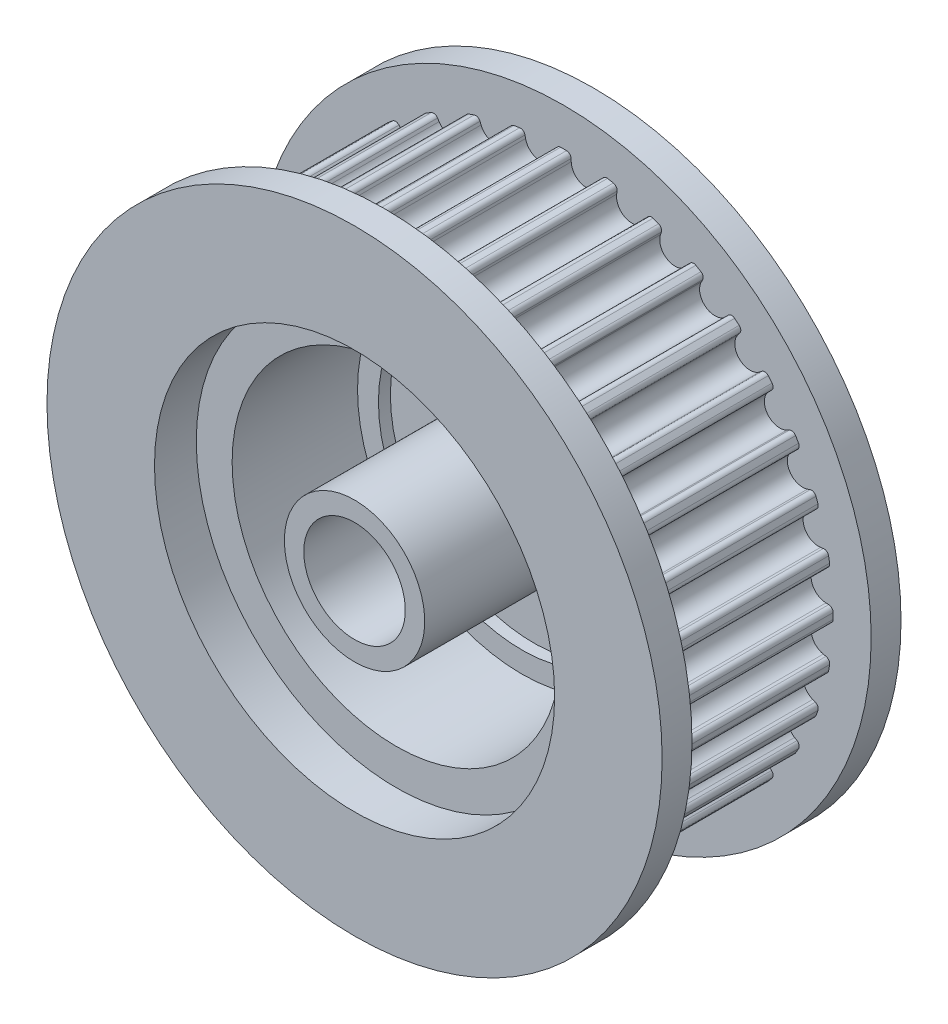
SolidWorks part; units mm, degrees
ref_plane "前视基准面" through (0, 0, 0) normal (0, 0, 1) x (1, 0, 0)
ref_plane "上视基准面" through (0, 0, 0) normal (0, 1, 0) x (1, 0, 0)
ref_plane "右视基准面" through (0, 0, 0) normal (1, 0, 0) x (0, 0, -1)
sketch "Sketch2" plane through (0, 0, 0) normal (0, 0, 1) x (1, 0, 0)
  circle A0 centre (0, 0) radius 45.15
  dimension "D1" = 90.3
extrude "Extrude1" add sketch "Sketch2" along normal mid plane 30
sketch "Sketch1" plane through (0, 0, 15) normal (0, 0, 1) x (1, 0, 0)
  line L0 (0, 0) -> (0, 45.835) construction
  line L1 (0, 0) -> (-3.9948, 45.6606) construction
  line L2 (-1.2656, 44.3946) -> (-1.2821, 43.9222)
  line L3 (-6.4627, 43.9399) -> (-6.3644, 43.4775)
  circle A0 centre (0, 0) radius 45.835 construction
  arc A1 (-0.4946, 45.1473) -> (-7.3526, 44.5473) centre (0, 0) ccw
  arc A2 (-6.3644, 43.4775) -> (-1.2821, 43.9222) centre (-3.8505, 44.0119) ccw
  arc A3 (-0.4946, 45.1473) -> (-1.2656, 44.3946) centre (-0.4861, 44.3673) ccw
  arc A4 (-7.3526, 44.5473) -> (-6.4627, 43.9399) centre (-7.2256, 43.7777) cw
  point P4 (45.6606, 3.9948)
  point P5 (44.2732, 11.863)
  point P6 (41.5406, 19.3707)
  point P7 (37.5458, 26.2899)
  point P8 (32.4102, 32.4102)
  point P9 (26.2899, 37.5458)
  point P10 (19.3707, 41.5406)
  point P11 (11.863, 44.2732)
  point P12 (3.9948, 45.6606)
  point P13 (-3.9948, 45.6606)
  point P14 (-11.863, 44.2732)
  point P15 (-19.3707, 41.5406)
  point P16 (-26.2899, 37.5458)
  point P17 (-32.4102, 32.4102)
  point P18 (-37.5458, 26.2899)
  point P19 (-41.5406, 19.3707)
  point P20 (-44.2732, 11.863)
  point P21 (-45.6606, 3.9948)
  point P22 (-45.6606, -3.9948)
  point P23 (-44.2732, -11.863)
  point P24 (-41.5406, -19.3707)
  point P25 (-37.5458, -26.2899)
  point P26 (-32.4102, -32.4102)
  point P27 (-26.2899, -37.5458)
  point P28 (-19.3707, -41.5406)
  point P29 (-11.863, -44.2732)
  point P30 (-3.9948, -45.6606)
  point P31 (3.9948, -45.6606)
  point P32 (11.863, -44.2732)
  point P33 (19.3707, -41.5406)
  point P34 (26.2899, -37.5458)
  point P35 (32.4102, -32.4102)
  point P36 (37.5458, -26.2899)
  point P37 (41.5406, -19.3707)
  point P38 (44.2732, -11.863)
  point P39 (45.6606, -3.9948)
  dimension "D1" = 91.67
  dimension "D2" = 90.3
  dimension "D3" = 5.14
  dimension "D4" = 3.54
  dimension "D5" = 1.56
  dimension "D6" = 7
extrude "Extrude2" cut sketch "Sketch1" against normal through all
pattern_circular "CirPattern1" count 36 over 360 about axis through (0, 0, 0) along (0, 0, 1) of "Extrude2"
sketch "Sketch3" plane through (0, 0, -15) normal (0, 0, -1) x (-1, 0, 0)
  circle A0 centre (0, 0) radius 51.5
  dimension "D1" = 103
extrude "Extrude3" add sketch "Sketch3" along normal blind 5
sketch "Sketch4" plane through (0, 0, 15) normal (0, 0, 1) x (1, 0, 0)
  circle A0 centre (0, 0) radius 51.5
  circle A1 centre (0, 0) radius 51.5 construction
extrude "Extrude4" add sketch "Sketch4" along normal blind 5
sketch "Sketch6" plane through (0, 0, 0) normal (0, 1, 0) x (1, 0, 0)
  line L0 (0, 20) -> (0, -20) construction
  line L1 (51.5, 20) -> (-51.5, 20) construction
  line L2 (-51.5, -20) -> (51.5, -20) construction
  line L3 (0, 20) -> (8.5, 20)
  line L4 (8.5, 20) -> (8.5, -20)
  line L5 (8.5, -20) -> (0, -20)
  line L6 (11.75, -20) -> (33.5, -20)
  line L9 (11.75, 10) -> (11.75, -20)
  line L11 (27.5, 8) -> (24, 8)
  line L12 (24, 8) -> (24, 10)
  line L13 (24, 10) -> (11.75, 10)
  line L15 (27.5, 8) -> (27.5, -13)
  line L16 (27.5, -13) -> (33.5, -13)
  line L17 (33.5, -13) -> (33.5, -20)
  line L18 (0, 20) -> (0, -20)
  dimension "D1" = 55
  dimension "D2" = 23.5
  dimension "D3" = 6
  dimension "D4" = 17
  dimension "D5" = 48
  dimension "D6" = 2
  dimension "D7" = 7
  dimension "D8" = 28
revolve "Cut-Revolve1" cut sketch "Sketch6" angle 360 about L0
